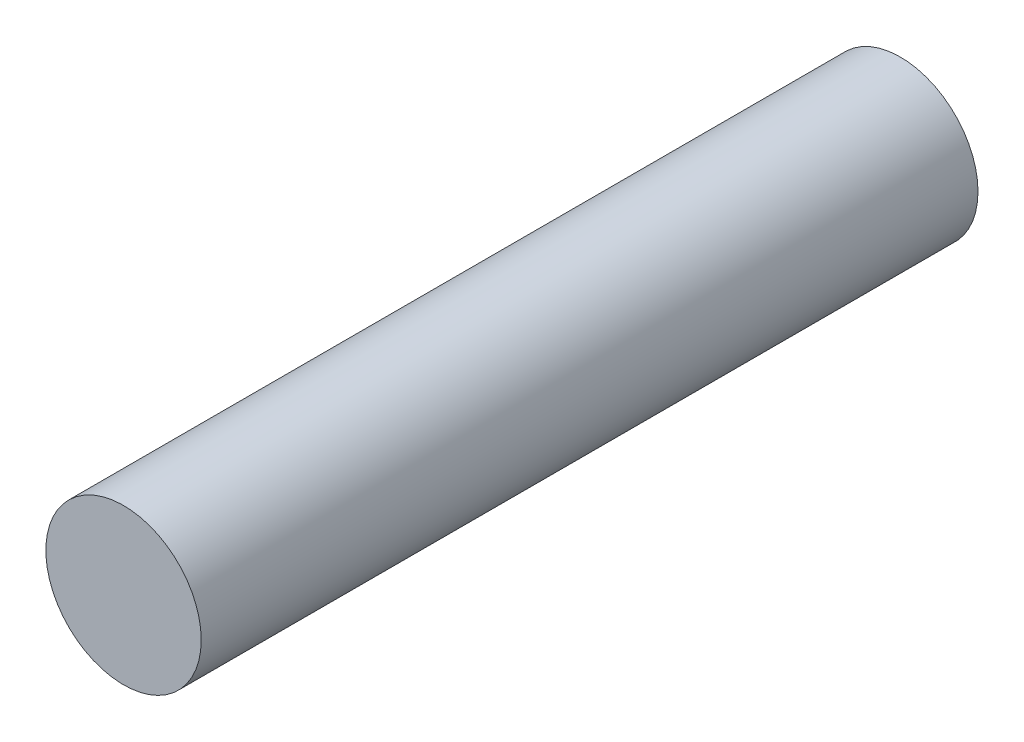
SolidWorks part; units mm, degrees
ref_plane "Alzado" through (0, 0, 0) normal (0, 0, 1) x (1, 0, 0)
ref_plane "Planta" through (0, 0, 0) normal (0, 1, 0) x (1, 0, 0)
ref_plane "Vista lateral" through (0, 0, 0) normal (1, 0, 0) x (0, 0, -1)
sketch "Croquis1" plane through (0, 0, 0) normal (0, 0, 1) x (1, 0, 0)
  circle A0 centre (0, 0) radius 1
  dimension "D1" = 2
extrude "Saliente-Extruir1" add sketch "Croquis1" along normal blind 10
